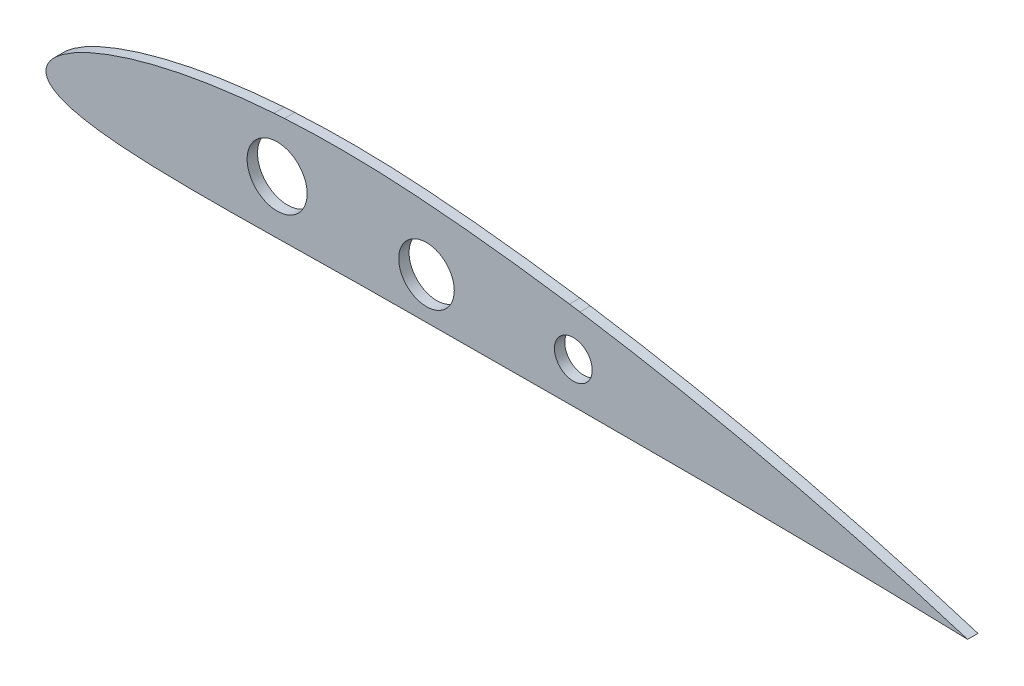
SolidWorks part; units mm, degrees
material "Фанера"
ref_plane "Front Plane" through (0, 0, 0) normal (0, 0, 1) x (1, 0, 0)
ref_plane "Top Plane" through (0, 0, 0) normal (0, 1, 0) x (1, 0, 0)
ref_plane "Right Plane" through (0, 0, 0) normal (1, 0, 0) x (0, 0, -1)
sketch "Эскиз1" plane through (0, 0, 0) normal (0, 0, 1) x (1, 0, 0)
  line L0 (150.3512, 128.259) -> (147.6767, 128.661)
  line L1 (255.981, 105.8183) -> (150.7263, 130.2251) construction
  line L2 (69.8251, 105.8135) -> (147.0441, 106.4426) construction
  line L3 (6.1919, 114.8477) -> (66.9719, 105.7712) construction
  line L4 (68.006, 135.3847) -> (6.1919, 114.8477) construction
  line L5 (68.3924, 133.4055) -> (14.7673, 115.5893) construction
  line L6 (69.8021, 107.8133) -> (147.0317, 108.4426) construction
  line L7 (147.8895, 130.6515) -> (70.8642, 135.5703) construction
  line L8 (67.001, 103.7714) -> (69.8554, 103.8137) construction
  line L9 (70.7405, 137.5665) -> (67.8703, 137.3801) construction
  line L10 (151.028, 132.2022) -> (148.1867, 132.6293) construction
  line L11 (147.0528, 104.4426) -> (149.9045, 104.4548) construction
  line L12 (147.6767, 128.661) -> (70.8653, 133.5662) construction
  line L13 (240.4166, 107.3743) -> (150.3512, 128.259) construction
  line L14 (149.8962, 106.4548) -> (255.959, 105.1887) construction
  line L15 (149.9039, 108.4548) -> (240.4166, 107.3743) construction
  line L16 (150.7263, 130.2251) -> (147.8895, 130.6515) construction
  line L17 (147.0441, 106.4426) -> (149.8962, 106.4548) construction
  line L18 (66.9719, 105.7712) -> (69.8251, 105.8135) construction
  line L19 (70.8642, 135.5703) -> (68.006, 135.3847) construction
  line L20 (67.1056, 107.7734) -> (69.8021, 107.8133) construction
  line L21 (70.8653, 133.5662) -> (68.3924, 133.4055) construction
  line L22 (147.0317, 108.4426) -> (149.9039, 108.4548) construction
  line L23 (14.7673, 115.5893) -> (67.1056, 107.7734) construction
  line L24 (150.6664, 129.8296) -> (147.8304, 130.2559)
  line L25 (70.8877, 135.171) -> (68.0343, 134.9857)
  line L26 (66.966, 106.1712) -> (69.8191, 106.2134)
  line L27 (147.0423, 106.8426) -> (149.8946, 106.8548)
  arc A0 (240.4166, 107.3743) -> (240.4166, 107.3743) centre (240.4166, 107.3743) ccw
  arc A1 (255.3129, 105.6068) -> (255.3129, 105.6068) centre (255.3129, 105.6068) ccw
  circle A2 centre (148.8681, 117.845) radius 5.1
  circle A3 centre (109.2326, 117.845) radius 7.5
  circle A4 centre (68.9168, 120.6369) radius 8.1
  arc A6 (256.3721, 103.1764) -> (256.8714, 107.636) centre (255.6552, 105.5145) ccw construction
  arc A8 (255.959, 105.1887) -> (255.981, 105.8183) centre (255.6552, 105.5145) ccw construction
  spline S0 degree 1 poles (147.8304, 130.2559) (70.8877, 135.171) knots 0 0 1 1 construction
  spline S1 degree 1 poles (68.0343, 134.9857) (6.5854, 114.7729) knots 0 0 1 1 construction
  spline S2 degree 1 poles (6.5854, 114.7729) (66.966, 106.1712) knots 0 0 1 1 construction
  spline S3 degree 1 poles (69.8191, 106.2134) (147.0423, 106.8426) knots 0 0 1 1 construction
  spline S4 degree 1 poles (149.8946, 106.8548) (255.3129, 105.6068) knots 0 0 1 1 construction
  spline S5 degree 1 poles (255.3129, 105.6068) (150.6664, 129.8296) knots 0 0 1 1 construction
  spline S6 degree 3 poles (147.8304, 130.2559) (141.4614, 131.1985) (128.6934, 132.8864) (112.6704, 134.4616) (99.827, 135.315) (86.964, 135.7313) (77.3083, 135.5495) (70.8877, 135.171) knots 0.429725 0.429725 0.429725 0.429725 0.504545 0.579365 0.616774 0.654184 0.729004 0.729004 0.729004 0.729004
  spline S7 degree 3 poles (68.0343, 134.9857) (62.4663, 134.5901) (54.1288, 133.7002) (43.1252, 131.8029) (34.9538, 129.9771) (26.9072, 127.676) (20.368, 125.2621) (15.3365, 122.8884) (11.7396, 120.808) (8.9915, 118.6964) (7.4817, 116.8862) (6.9154, 115.8582) (6.7079, 115.2743) (6.6255, 114.9369) (6.5854, 114.7729) knots 0.740091 0.740091 0.740091 0.740091 0.805048 0.837527 0.870006 0.902484 0.934963 0.951202 0.967442 0.983681 0.991801 0.995861 0.99789 0.99992 0.99992 0.99992 0.99992
  spline S8 degree 3 poles (6.5854, 114.7729) (6.5637, 114.6143) (6.519, 114.2854) (6.5148, 113.7109) (6.7419, 112.6615) (7.6602, 111.4099) (9.2591, 110.3083) (11.0446, 109.4874) (12.9222, 108.8501) (15.4901, 108.1728) (18.7685, 107.5586) (22.7454, 107.0432) (28.0773, 106.5574) (34.7696, 106.2135) (42.8135, 106.0372) (50.8627, 106.0061) (58.9136, 106.0623) (64.282, 106.1325) (66.966, 106.1712) knots 0.000081 0.000081 0.000081 0.000081 0.002067 0.004053 0.008026 0.01597 0.023915 0.031859 0.039804 0.047748 0.063637 0.079526 0.095416 0.127194 0.158972 0.19075 0.222528 0.254306 0.254306 0.254306 0.254306
  spline S9 degree 3 poles (69.8191, 106.2134) (76.2539, 106.311) (85.9048, 106.4721) (98.7779, 106.6108) (111.6511, 106.6495) (127.7354, 106.7325) (140.607, 106.8137) (147.0423, 106.8426) knots 0.265565 0.265565 0.265565 0.265565 0.341733 0.379817 0.417901 0.494069 0.570237 0.570237 0.570237 0.570237
  spline S10 degree 3 poles (149.8946, 106.8548) (158.6803, 106.89) (176.2516, 106.9163) (202.6097, 106.7306) (228.9647, 106.2926) (246.5305, 105.8506) (255.3129, 105.6068) knots 0.58149 0.58149 0.58149 0.58149 0.685469 0.789448 0.893427 0.997406 0.997406 0.997406 0.997406
  spline S11 degree 3 poles (255.3129, 105.6068) (246.7563, 108.2609) (229.5444, 113.257) (203.4702, 119.7998) (177.1786, 125.4044) (159.5222, 128.478) (150.6664, 129.8296) knots 0.002228 0.002228 0.002228 0.002228 0.106325 0.210423 0.31452 0.418617 0.418617 0.418617 0.418617
  spline S12 degree 3 poles (4.2245, 115.2218) (4.2126, 115.1351) (4.1901, 114.9728) (4.1369, 114.5596) (4.0997, 113.8715) (4.1934, 113.0746) (4.4478, 112.0722) (5.0329, 110.8962) (5.9577, 109.8121) (6.9592, 108.9756) (8.333, 108.0935) (10.0616, 107.291) (12.1329, 106.5788) (14.8842, 105.8458) (18.3089, 105.1999) (22.402, 104.6657) (26.4841, 104.2911) (30.5571, 104.0277) (35.978, 103.7862) (42.7402, 103.6379) (50.8379, 103.6058) (58.9249, 103.6622) (64.3084, 103.7327) (67.001, 103.7714) knots -0.000405 -0.000405 -0.000405 -0.000405 0.00059 0.001585 0.003575 0.005565 0.007555 0.011535 0.015514 0.019494 0.023474 0.031434 0.039394 0.047354 0.063273 0.079193 0.095112 0.111032 0.126952 0.158791 0.19063 0.222469 0.254308 0.254308 0.254308 0.254308 construction
  spline S13 degree 3 poles (67.8703, 137.3801) (65.0503, 137.1797) (59.4186, 136.6785) (50.9968, 135.5967) (42.6198, 134.1508) (34.309, 132.2908) (27.4644, 130.3322) (22.0663, 128.4455) (18.0689, 126.8357) (14.1437, 124.9752) (10.9598, 123.1311) (8.5154, 121.3532) (7.0522, 120.0467) (5.9644, 118.8218) (5.3324, 117.9305) (4.8996, 117.1691) (4.5854, 116.5037) (4.3875, 115.8781) (4.2866, 115.4769) (4.246, 115.3096) (4.2245, 115.2218) knots 0.740067 0.740067 0.740067 0.740067 0.772609 0.80515 0.837691 0.870232 0.902774 0.919044 0.935315 0.951586 0.967856 0.975992 0.984127 0.988195 0.992262 0.994296 0.99633 0.998364 0.999381 1.000398 1.000398 1.000398 1.000398 construction
  spline S14 degree 3 poles (148.1867, 132.6293) (141.7912, 133.5759) (128.9685, 135.2709) (112.884, 136.8527) (99.9444, 137.7126) (86.9715, 138.1325) (77.2213, 137.9485) (70.7405, 137.5665) knots 0.429706 0.429706 0.429706 0.429706 0.504536 0.579367 0.616782 0.654197 0.729027 0.729027 0.729027 0.729027 construction
  spline S15 degree 3 poles (256.8714, 107.636) (248.2169, 110.3216) (230.8173, 115.4068) (204.446, 122.039) (177.8555, 127.7216) (159.9886, 130.8346) (151.028, 132.2022) knots -0.001207 -0.001207 -0.001207 -0.001207 0.10375 0.208706 0.313663 0.418619 0.418619 0.418619 0.418619 construction
  spline S16 degree 3 poles (149.9045, 104.4548) (158.7785, 104.4903) (176.5281, 104.5165) (203.1441, 104.3248) (229.757, 103.8766) (247.5013, 103.4229) (256.3721, 103.1764) knots 0.581491 0.581491 0.581491 0.581491 0.686581 0.79167 0.89676 1.001849 1.001849 1.001849 1.001849 construction
  spline S17 degree 3 poles (69.8554, 103.8137) (76.2881, 103.9112) (85.9421, 104.0724) (98.7946, 104.2108) (111.6509, 104.2495) (127.7557, 104.3325) (140.6187, 104.4137) (147.0528, 104.4426) knots 0.265565 0.265565 0.265565 0.265565 0.341733 0.379817 0.4179 0.494068 0.570236 0.570236 0.570236 0.570236 construction
  spline S24 degree 3 poles (255.981, 105.8183) (255.1452, 106.0776) (252.7344, 106.8257) (248.4483, 108.1259) (242.96, 109.7477) (236.9465, 111.469) (230.6793, 113.2037) (224.3094, 114.9057) (217.8951, 116.5587) (211.4569, 118.157) (205.0023, 119.6987) (198.5346, 121.1828) (192.0557, 122.6086) (185.5671, 123.9752) (179.0705, 125.2817) (172.5672, 126.5268) (166.0589, 127.7093) (159.5471, 128.8277) (154.4349, 129.6536) (151.4938, 130.108) (150.7263, 130.2251) knots 0 0 0 0 0.010162 0.029313 0.052012 0.076619 0.101948 0.127526 0.153184 0.178868 0.204558 0.230246 0.255926 0.281594 0.307246 0.332878 0.358485 0.384061 0.409603 0.418619 0.418619 0.418619 0.418619 construction
  spline S25 degree 3 poles (149.8962, 106.4548) (151.0697, 106.4595) (154.5381, 106.4723) (160.2987, 106.4873) (167.1755, 106.4936) (174.0453, 106.4866) (180.9094, 106.465) (187.7693, 106.4278) (194.6263, 106.3745) (201.4814, 106.3045) (208.3355, 106.2177) (217.4659, 106.0799) (226.5694, 105.9098) (235.5825, 105.7122) (242.0508, 105.5578) (247.9425, 105.407) (252.5192, 105.2842) (255.0798, 105.2131) (255.959, 105.1887) knots 0.58149 0.58149 0.58149 0.58149 0.59538 0.622543 0.649673 0.676775 0.703855 0.730919 0.757971 0.785018 0.812062 0.839103 0.893099 0.919831 0.94581 0.969681 0.98959 1 1 1 1 construction
  spline S26 degree 3 poles (69.8251, 105.8135) (70.1857, 105.8189) (72.8406, 105.8595) (77.7874, 105.9382) (84.6559, 106.0429) (91.5023, 106.1327) (98.3304, 106.2005) (105.1587, 106.2352) (112.0058, 106.2499) (118.883, 106.2851) (125.7838, 106.3242) (132.6989, 106.366) (139.7863, 106.4072) (144.5679, 106.4315) (147.0441, 106.4426) knots 0.265565 0.265565 0.265565 0.265565 0.269834 0.296993 0.324123 0.351139 0.378036 0.404946 0.431961 0.459078 0.486347 0.513641 0.540929 0.570237 0.570237 0.570237 0.570237 construction
  spline S27 degree 3 poles (6.1919, 114.8477) (6.158, 114.6008) (6.0902, 114.1069) (6.1694, 113.3417) (6.4146, 112.5783) (6.8536, 111.8363) (7.4788, 111.1398) (8.2841, 110.4896) (9.2784, 109.8798) (10.4882, 109.2993) (11.964, 108.7389) (13.7853, 108.1919) (16.0678, 107.6555) (18.9581, 107.1364) (22.5962, 106.6558) (27.0464, 106.2459) (32.2488, 105.9348) (38.0427, 105.7329) (44.2433, 105.6313) (50.7063, 105.6105) (57.3406, 105.6492) (62.7802, 105.7125) (66.003, 105.7573) (66.9719, 105.7712) knots 0 0 0 0 0.002941 0.005884 0.009016 0.012365 0.016008 0.020037 0.024574 0.029784 0.035897 0.04324 0.052276 0.063635 0.077983 0.095698 0.11652 0.139661 0.164312 0.189919 0.216157 0.242838 0.254307 0.254307 0.254307 0.254307 construction
  spline S28 degree 3 poles (68.006, 135.3847) (66.8126, 135.2999) (63.6237, 135.0487) (58.4686, 134.5329) (52.5772, 133.7756) (46.793, 132.8557) (41.1539, 131.7728) (35.7197, 130.533) (30.584, 129.1556) (25.8745, 127.6815) (21.7278, 126.1743) (18.2359, 124.7076) (15.4053, 123.3395) (13.1621, 122.0961) (11.3946, 120.9731) (9.9961, 119.9509) (8.8828, 119.0062) (7.9974, 118.1179) (7.2991, 117.2701) (6.7718, 116.4486) (6.3879, 115.6507) (6.2553, 115.1075) (6.1919, 114.8477) knots 0.740091 0.740091 0.740091 0.740091 0.753983 0.777235 0.800246 0.822951 0.845237 0.866916 0.887662 0.906968 0.924203 0.938879 0.950932 0.960693 0.968647 0.975233 0.980795 0.985584 0.989782 0.993521 0.996902 1 1 1 1 construction
  spline S29 degree 3 poles (147.8895, 130.6515) (147.4311, 130.7194) (144.8039, 131.1052) (140.0082, 131.7785) (133.5004, 132.6198) (127.0013, 133.3854) (120.5131, 134.0729) (114.0543, 134.6743) (107.657, 135.196) (101.3381, 135.605) (95.0879, 135.8768) (88.882, 136.0122) (82.7096, 136.0098) (76.7059, 135.8678) (72.7625, 135.6822) (70.8642, 135.5703) knots 0.429724 0.429724 0.429724 0.429724 0.435104 0.460559 0.485959 0.511303 0.536552 0.561723 0.586629 0.611085 0.635251 0.659272 0.683164 0.706922 0.729004 0.729004 0.729004 0.729004 construction
  point P54 (109.2326, 117.845)
  dimension "D1" = 16.2
  dimension "D2" = 10.2
  dimension "D4" = 15
  dimension "D3" = 0.4
  dimension "D5" = 2
extrude "Бобышка-Вытянуть1" add sketch "Эскиз1" along normal mid plane 2.8 contours S10 S11 L24 S6 L25 S7 S8 L26 S9 L27 A2 A4
